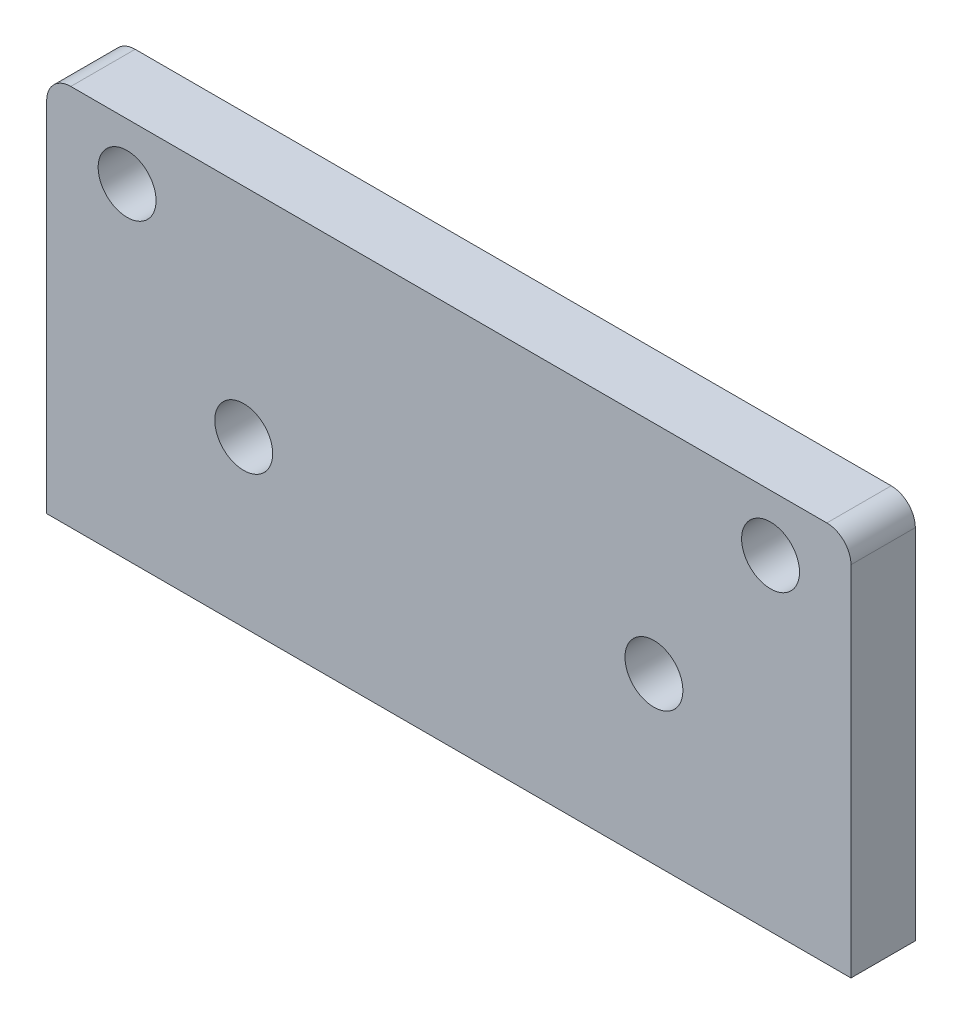
SolidWorks part; units mm, degrees
ref_plane "Front Plane" through (0, 0, 0) normal (0, 0, 1) x (1, 0, 0)
ref_plane "Top Plane" through (0, 0, 0) normal (0, 1, 0) x (1, 0, 0)
ref_plane "Right Plane" through (0, 0, 0) normal (1, 0, 0) x (0, 0, -1)
sketch "Sketch1" plane through (0, 0, 0) normal (0, 0, 1) x (1, 0, 0)
  line L1 (-25, 11.875) -> (25, 11.875)
  line L2 (-25, 11.875) -> (-25, -11.875)
  line L3 (-25, -11.875) -> (25, -11.875)
  line L4 (25, 11.875) -> (25, -11.875)
  line L5 (-25, 11.875) -> (25, -11.875) construction
  line L6 (-25, -11.875) -> (25, 11.875) construction
  point P0 (0, 0)
  dimension "D1" = 50
  dimension "D2" = 23.75
extrude "Boss-Extrude1" add sketch "Sketch1" along normal blind 4
fillet "Fillet1" radius 1.5 2 edges at (-25, 11.875, 2) (25, 11.875, 2)
sketch "Sketch2" plane through (0, 0, 4) normal (0, 0, 1) x (1, 0, 0)
  circle A0 centre (-12.75, -1.625) radius 1.8 construction
  circle A1 centre (-20, 8.375) radius 1.8 construction
  circle A2 centre (12.75, -1.625) radius 1.8 construction
  circle A3 centre (20, 8.375) radius 1.8 construction
  circle A4 centre (-12.75, -1.625) radius 1.8
  circle A5 centre (-20, 8.375) radius 1.8
  circle A6 centre (12.75, -1.625) radius 1.8
  circle A7 centre (20, 8.375) radius 1.8
extrude "Cut-Extrude1" cut sketch "Sketch2" against normal through all
